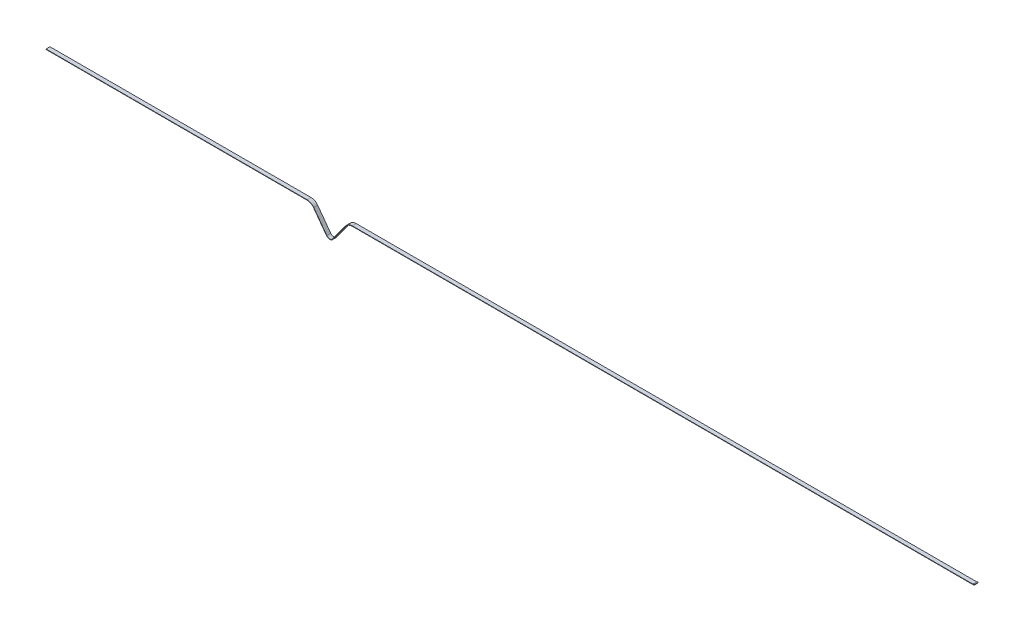
SolidWorks part; units mm, degrees
ref_plane "Front Plane" through (0, 0, 0) normal (0, 0, 1) x (1, 0, 0)
ref_plane "Top Plane" through (0, 0, 0) normal (0, 1, 0) x (1, 0, 0)
ref_plane "Right Plane" through (0, 0, 0) normal (1, 0, 0) x (0, 0, -1)
sketch "Sketch1" plane through (0, 0, 0) normal (1, 0, 0) x (0, 0, -1)
  line L1 (0, 0) -> (6, 0)
  line L2 (0, 0) -> (0, 0.63)
  line L3 (0, 0.63) -> (6, 0.63)
  line L4 (6, 0) -> (6, 0.63)
  dimension "D1" = 0.63
  dimension "D2" = 6
sketch "Sketch2" plane through (0, 0, 0) normal (0, 0, 1) x (1, 0, 0)
  line L0 (0, 0) -> (-953.0122, 0)
  line L1 (-962.6449, -4.8779) -> (-982.6571, -32.1359)
  line L2 (-992.5074, -32.1359) -> (-1012.5196, -4.8779)
  line L3 (-1022.1522, 0) -> (-1422.4, 0)
  arc A0 (-953.0122, 0) -> (-962.6449, -4.8779) centre (-953.0122, -11.95) ccw
  arc A1 (-982.6571, -32.1359) -> (-992.5074, -32.1359) centre (-987.5822, -28.52) cw
  arc A2 (-1012.5196, -4.8779) -> (-1022.1522, 0) centre (-1022.1522, -11.95) ccw
  circle A3 centre (-1022.1522, -11.95) radius 11.95 construction
  circle A4 centre (-987.5822, -28.52) radius 6.11 construction
  circle A5 centre (-953.0122, -11.95) radius 11.95 construction
  dimension "D1" = 6.11
  dimension "D4" = 1422.4
sweep "Sweep1" add profiles "Sketch1" path "Sketch2"
sketch "Sketch3" plane through (0, 0, 0) normal (0, 0, 1) x (1, 0, 0)
  line L0 (0, 0.63) -> (-953.0122, 0.63) construction
  line L1 (-1.5, 0.63) -> (-1.5, 0)
  line L2 (0, 0) -> (-953.0122, 0) construction
  line L3 (-1.5, 0) -> (0, 0)
  line L4 (0, 0) -> (0, 0.63)
  arc A1 (0, 0.63) -> (-1.5, 0.63) centre (-0.75, 0.63) ccw
  dimension "D1" = 0.75
extrude "Boss-Extrude1" add sketch "Sketch3" against normal through all
pattern_curve "CrvPattern1" [suppressed] parameters "D1"=2000, "D3"=2, "D2"=1, "D4"=10
